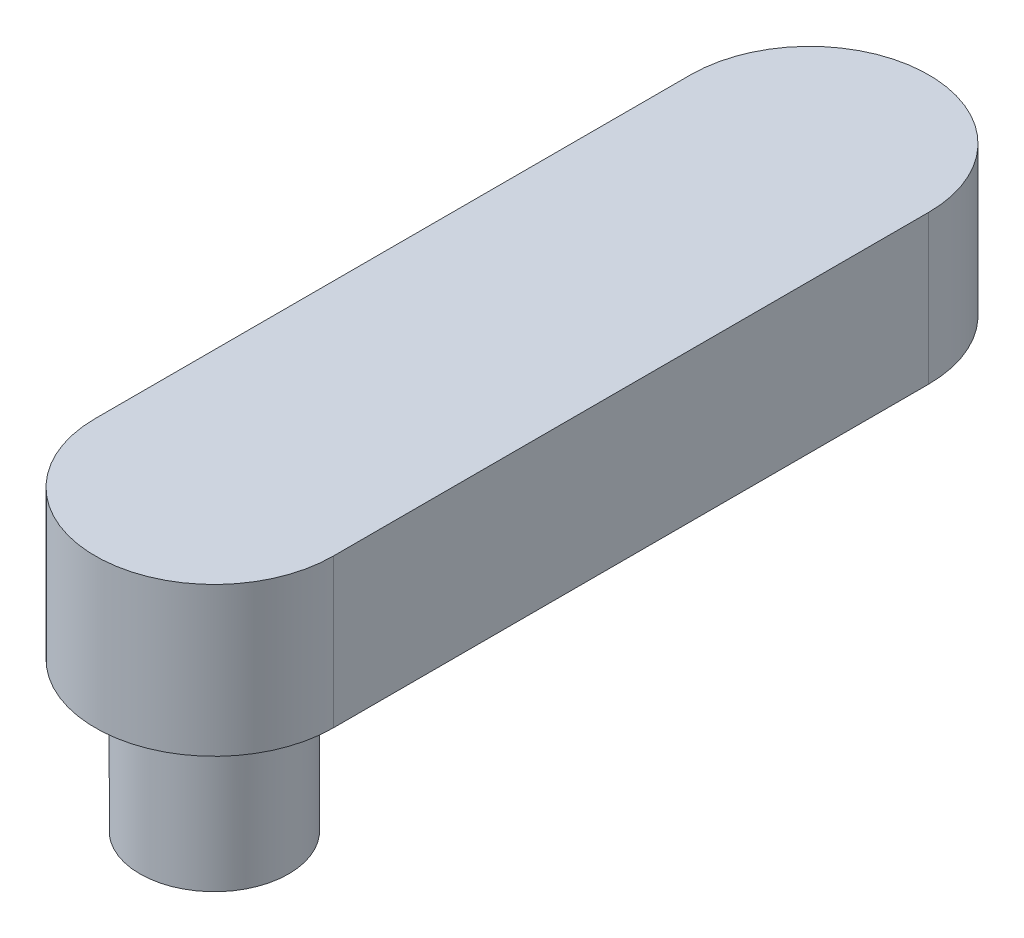
SolidWorks part; units mm, degrees
ref_plane "Front Plane" through (0, 0, 0) normal (0, 0, 1) x (1, 0, 0)
ref_plane "Top Plane" through (0, 0, 0) normal (0, 1, 0) x (1, 0, 0)
ref_plane "Right Plane" through (0, 0, 0) normal (1, 0, 0) x (0, 0, -1)
sketch "Sketch1" plane through (0, 0, 0) normal (0, 1, 0) x (1, 0, 0)
  line L0 (0, 20) -> (0, -20) construction
  line L1 (8, 20) -> (8, -20)
  line L2 (-8, 20) -> (-8, -20)
  arc A0 (8, 20) -> (-8, 20) centre (0, 20) ccw
  arc A1 (-8, -20) -> (8, -20) centre (0, -20) ccw
  point P3 (0, 0)
  point P8 (0, 0)
  dimension "D2" = 8
  dimension "D1" = 40
extrude "Boss-Extrude1" add sketch "Sketch1" along normal blind 10
sketch "Sketch2" plane through (0, 0, 0) normal (0, -1, 0) x (1, 0, 0)
  circle A0 centre (0, 20) radius 5
  dimension "D1" = 10
  dimension "D2" = 20
extrude "Boss-Extrude2" add sketch "Sketch2" along normal blind 10
